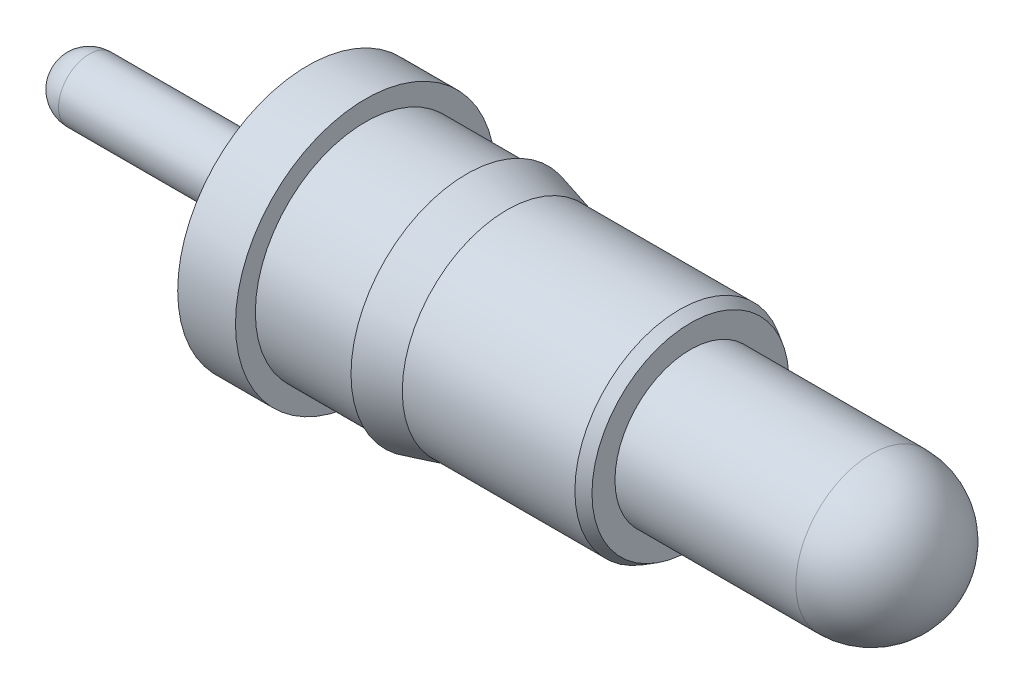
SolidWorks part; units mm, degrees
material "Brass Alloy 385"
ref_plane "Front Plane" through (0, 0, 0) normal (0, 0, 1) x (1, 0, 0)
ref_plane "Top Plane" through (0, 0, 0) normal (0, 1, 0) x (1, 0, 0)
ref_plane "Right Plane" through (0, 0, 0) normal (1, 0, 0) x (0, 0, -1)
sketch "Sketch1" plane through (0, 0, 0) normal (0, 0, 1) x (1, 0, 0)
  line L0 (0, 0) -> (5.7445, 0) construction
  line L1 (0, 0) -> (6.2484, 0)
  line L2 (1.6764, 0.2159) -> (0.2159, 0.2159)
  line L3 (1.7526, 0.9144) -> (1.7526, 0.2921)
  line L5 (1.7526, 0.9144) -> (2.159, 0.9144)
  line L6 (2.159, 0.9144) -> (2.159, 0.7747)
  line L7 (2.159, 0.7747) -> (2.8702, 0.7747)
  line L8 (2.8702, 0.7747) -> (2.8702, 0.8128)
  line L9 (2.8702, 0.8128) -> (3.1546, 0.7366)
  line L10 (3.1546, 0.7366) -> (4.3688, 0.7366)
  line L11 (4.3688, 0.7366) -> (4.445, 0.6926)
  line L12 (4.445, 0.6926) -> (4.445, 0.5309)
  line L13 (4.445, 0.5309) -> (5.7175, 0.5309)
  arc A2 (6.2484, 0) -> (5.7175, 0.5309) centre (5.7175, 0) ccw
  arc A3 (0.2159, 0.2159) -> (0, 0) centre (0.2159, 0) ccw
  arc A5 (1.6764, 0.2159) -> (1.7526, 0.2921) centre (1.6764, 0.2921) ccw
  dimension "D1" = 0.0762
  dimension "D15" = 0.5309
  dimension "D12" = 0.2159
  dimension "D2" = 1.0617
  dimension "D3" = 1.4732
  dimension "D4" = 1.6256
  dimension "D5" = 1.5494
  dimension "D6" = 1.8288
  dimension "D7" = 0.4318
  dimension "D8" = 15
  dimension "D9" = 30
  dimension "D10" = 0.4064
  dimension "D11" = 0.7112
  dimension "B" = 2.6924
  dimension "D13" = 1.7526
  dimension "A" = 4.4958
  dimension "D16" = 0.0762
revolve "Revolve1" add sketch "Sketch1" angle 360 about L0
